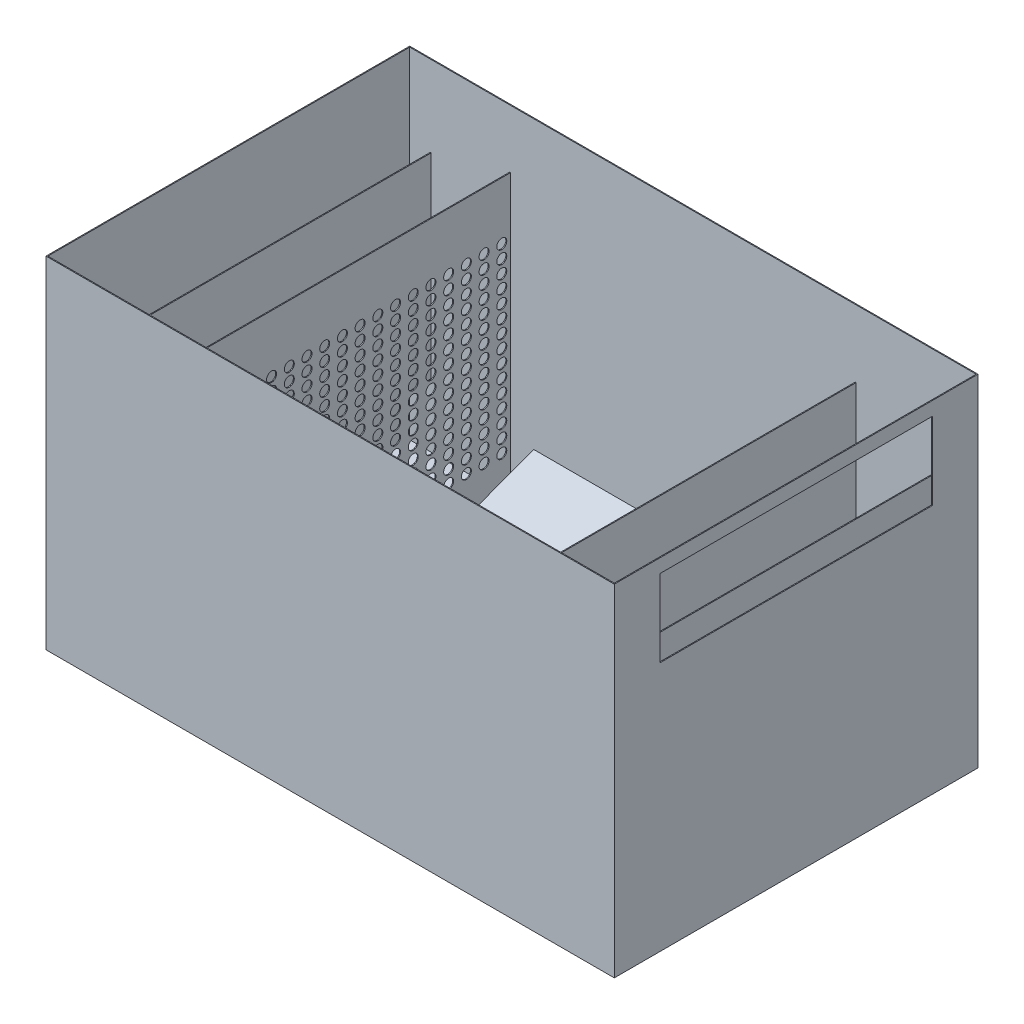
SolidWorks part; units mm, degrees
ref_plane "Спереди" through (0, 0, 0) normal (0, 0, 1) x (1, 0, 0)
ref_plane "Сверху" through (0, 0, 0) normal (0, 1, 0) x (1, 0, 0)
ref_plane "Справа" through (0, 0, 0) normal (1, 0, 0) x (0, 0, -1)
sketch "MASTER_FOOTPRINT" plane through (0, 0, 0) normal (0, 1, 0) x (1, 0, 0)
  line L1 (0, 0) -> (1250, 0)
  line L2 (0, 0) -> (0, 800)
  line L3 (0, 800) -> (1250, 800)
  line L4 (1250, 0) -> (1250, 800)
  dimension "D1" = 1250
  dimension "D2" = 800
extrude "BATH_BASE_PLATE" add sketch "MASTER_FOOTPRINT" along normal blind 750
shell "BATH_SHELL_2MM" thickness 2
sketch "Эскиз1" plane through (0, 0, 0) normal (1, 0, 0) x (0, 0, -1)
  circle A0 centre (400, 420) radius 50
extrude "INLET_D100_OPENING" cut sketch "Эскиз1" along normal blind 10
sketch "Эскиз2" plane through (0, 0, 0) normal (1, 0, 0) x (0, 0, -1)
  line L1 (80, 220) -> (720, 220)
  line L2 (80, 220) -> (80, 650)
  line L3 (80, 650) -> (720, 650)
  line L4 (720, 220) -> (720, 650)
extrude "INLET_IMPACT_BAFFLE" add sketch "Эскиз2" along normal blind 2 from offset 125 separate body
sketch "Эскиз3" plane through (0, 0, 0) normal (1, 0, 0) x (0, 0, -1)
  line L1 (30, 2) -> (770, 2)
  line L2 (30, 2) -> (30, 650)
  line L3 (30, 650) -> (770, 650)
  line L4 (770, 2) -> (770, 650)
  circle A0 centre (49.4737, 125) radius 11
  circle A1 centre (49.4737, 153.5) radius 11
  circle A2 centre (49.4737, 182) radius 11
  circle A3 centre (49.4737, 210.5) radius 11
  circle A4 centre (49.4737, 239) radius 11
  circle A5 centre (49.4737, 267.5) radius 11
  circle A6 centre (49.4737, 296) radius 11
  circle A7 centre (49.4737, 324.5) radius 11
  circle A8 centre (49.4737, 353) radius 11
  circle A9 centre (49.4737, 381.5) radius 11
  circle A10 centre (49.4737, 410) radius 11
  circle A11 centre (49.4737, 438.5) radius 11
  circle A12 centre (49.4737, 467) radius 11
  circle A13 centre (49.4737, 495.5) radius 11
  circle A14 centre (49.4737, 524) radius 11
  circle A15 centre (88.4211, 125) radius 11
  circle A16 centre (88.4211, 153.5) radius 11
  circle A17 centre (88.4211, 182) radius 11
  circle A18 centre (88.4211, 210.5) radius 11
  circle A19 centre (88.4211, 239) radius 11
  circle A20 centre (88.4211, 267.5) radius 11
  circle A21 centre (88.4211, 296) radius 11
  circle A22 centre (88.4211, 324.5) radius 11
  circle A23 centre (88.4211, 353) radius 11
  circle A24 centre (88.4211, 381.5) radius 11
  circle A25 centre (88.4211, 410) radius 11
  circle A26 centre (88.4211, 438.5) radius 11
  circle A27 centre (88.4211, 467) radius 11
  circle A28 centre (88.4211, 495.5) radius 11
  circle A29 centre (88.4211, 524) radius 11
  circle A30 centre (127.3684, 125) radius 11
  circle A31 centre (127.3684, 153.5) radius 11
  circle A32 centre (127.3684, 182) radius 11
  circle A33 centre (127.3684, 210.5) radius 11
  circle A34 centre (127.3684, 239) radius 11
  circle A35 centre (127.3684, 267.5) radius 11
  circle A36 centre (127.3684, 296) radius 11
  circle A37 centre (127.3684, 324.5) radius 11
  circle A38 centre (127.3684, 353) radius 11
  circle A39 centre (127.3684, 381.5) radius 11
  circle A40 centre (127.3684, 410) radius 11
  circle A41 centre (127.3684, 438.5) radius 11
  circle A42 centre (127.3684, 467) radius 11
  circle A43 centre (127.3684, 495.5) radius 11
  circle A44 centre (127.3684, 524) radius 11
  circle A45 centre (166.3158, 125) radius 11
  circle A46 centre (166.3158, 153.5) radius 11
  circle A47 centre (166.3158, 182) radius 11
  circle A48 centre (166.3158, 210.5) radius 11
  circle A49 centre (166.3158, 239) radius 11
  circle A50 centre (166.3158, 267.5) radius 11
  circle A51 centre (166.3158, 296) radius 11
  circle A52 centre (166.3158, 324.5) radius 11
  circle A53 centre (166.3158, 353) radius 11
  circle A54 centre (166.3158, 381.5) radius 11
  circle A55 centre (166.3158, 410) radius 11
  circle A56 centre (166.3158, 438.5) radius 11
  circle A57 centre (166.3158, 467) radius 11
  circle A58 centre (166.3158, 495.5) radius 11
  circle A59 centre (166.3158, 524) radius 11
  circle A60 centre (205.2632, 125) radius 11
  circle A61 centre (205.2632, 153.5) radius 11
  circle A62 centre (205.2632, 182) radius 11
  circle A63 centre (205.2632, 210.5) radius 11
  circle A64 centre (205.2632, 239) radius 11
  circle A65 centre (205.2632, 267.5) radius 11
  circle A66 centre (205.2632, 296) radius 11
  circle A67 centre (205.2632, 324.5) radius 11
  circle A68 centre (205.2632, 353) radius 11
  circle A69 centre (205.2632, 381.5) radius 11
  circle A70 centre (205.2632, 410) radius 11
  circle A71 centre (205.2632, 438.5) radius 11
  circle A72 centre (205.2632, 467) radius 11
  circle A73 centre (205.2632, 495.5) radius 11
  circle A74 centre (205.2632, 524) radius 11
  circle A75 centre (244.2105, 125) radius 11
  circle A76 centre (244.2105, 153.5) radius 11
  circle A77 centre (244.2105, 182) radius 11
  circle A78 centre (244.2105, 210.5) radius 11
  circle A79 centre (244.2105, 239) radius 11
  circle A80 centre (244.2105, 267.5) radius 11
  circle A81 centre (244.2105, 296) radius 11
  circle A82 centre (244.2105, 324.5) radius 11
  circle A83 centre (244.2105, 353) radius 11
  circle A84 centre (244.2105, 381.5) radius 11
  circle A85 centre (244.2105, 410) radius 11
  circle A86 centre (244.2105, 438.5) radius 11
  circle A87 centre (244.2105, 467) radius 11
  circle A88 centre (244.2105, 495.5) radius 11
  circle A89 centre (244.2105, 524) radius 11
  circle A90 centre (283.1579, 125) radius 11
  circle A91 centre (283.1579, 153.5) radius 11
  circle A92 centre (283.1579, 182) radius 11
  circle A93 centre (283.1579, 210.5) radius 11
  circle A94 centre (283.1579, 239) radius 11
  circle A95 centre (283.1579, 267.5) radius 11
  circle A96 centre (283.1579, 296) radius 11
  circle A97 centre (283.1579, 324.5) radius 11
  circle A98 centre (283.1579, 353) radius 11
  circle A99 centre (283.1579, 381.5) radius 11
  circle A100 centre (283.1579, 410) radius 11
  circle A101 centre (283.1579, 438.5) radius 11
  circle A102 centre (283.1579, 467) radius 11
  circle A103 centre (283.1579, 495.5) radius 11
  circle A104 centre (283.1579, 524) radius 11
  circle A105 centre (322.1053, 125) radius 11
  circle A106 centre (322.1053, 153.5) radius 11
  circle A107 centre (322.1053, 182) radius 11
  circle A108 centre (322.1053, 210.5) radius 11
  circle A109 centre (322.1053, 239) radius 11
  circle A110 centre (322.1053, 267.5) radius 11
  circle A111 centre (322.1053, 296) radius 11
  circle A112 centre (322.1053, 324.5) radius 11
  circle A113 centre (322.1053, 353) radius 11
  circle A114 centre (322.1053, 381.5) radius 11
  circle A115 centre (322.1053, 410) radius 11
  circle A116 centre (322.1053, 438.5) radius 11
  circle A117 centre (322.1053, 467) radius 11
  circle A118 centre (322.1053, 495.5) radius 11
  circle A119 centre (322.1053, 524) radius 11
  circle A120 centre (361.0526, 125) radius 11
  circle A121 centre (361.0526, 153.5) radius 11
  circle A122 centre (361.0526, 182) radius 11
  circle A123 centre (361.0526, 210.5) radius 11
  circle A124 centre (361.0526, 239) radius 11
  circle A125 centre (361.0526, 267.5) radius 11
  circle A126 centre (361.0526, 296) radius 11
  circle A127 centre (361.0526, 324.5) radius 11
  circle A128 centre (361.0526, 353) radius 11
  circle A129 centre (361.0526, 381.5) radius 11
  circle A130 centre (361.0526, 410) radius 11
  circle A131 centre (361.0526, 438.5) radius 11
  circle A132 centre (361.0526, 467) radius 11
  circle A133 centre (361.0526, 495.5) radius 11
  circle A134 centre (361.0526, 524) radius 11
  circle A135 centre (400, 125) radius 11
  circle A136 centre (400, 153.5) radius 11
  circle A137 centre (400, 182) radius 11
  circle A138 centre (400, 210.5) radius 11
  circle A139 centre (400, 239) radius 11
  circle A140 centre (400, 267.5) radius 11
  circle A141 centre (400, 296) radius 11
  circle A142 centre (400, 324.5) radius 11
  circle A143 centre (400, 353) radius 11
  circle A144 centre (400, 381.5) radius 11
  circle A145 centre (400, 410) radius 11
  circle A146 centre (400, 438.5) radius 11
  circle A147 centre (400, 467) radius 11
  circle A148 centre (400, 495.5) radius 11
  circle A149 centre (400, 524) radius 11
  circle A150 centre (438.9474, 125) radius 11
  circle A151 centre (438.9474, 153.5) radius 11
  circle A152 centre (438.9474, 182) radius 11
  circle A153 centre (438.9474, 210.5) radius 11
  circle A154 centre (438.9474, 239) radius 11
  circle A155 centre (438.9474, 267.5) radius 11
  circle A156 centre (438.9474, 296) radius 11
  circle A157 centre (438.9474, 324.5) radius 11
  circle A158 centre (438.9474, 353) radius 11
  circle A159 centre (438.9474, 381.5) radius 11
  circle A160 centre (438.9474, 410) radius 11
  circle A161 centre (438.9474, 438.5) radius 11
  circle A162 centre (438.9474, 467) radius 11
  circle A163 centre (438.9474, 495.5) radius 11
  circle A164 centre (438.9474, 524) radius 11
  circle A165 centre (477.8947, 125) radius 11
  circle A166 centre (477.8947, 153.5) radius 11
  circle A167 centre (477.8947, 182) radius 11
  circle A168 centre (477.8947, 210.5) radius 11
  circle A169 centre (477.8947, 239) radius 11
  circle A170 centre (477.8947, 267.5) radius 11
  circle A171 centre (477.8947, 296) radius 11
  circle A172 centre (477.8947, 324.5) radius 11
  circle A173 centre (477.8947, 353) radius 11
  circle A174 centre (477.8947, 381.5) radius 11
  circle A175 centre (477.8947, 410) radius 11
  circle A176 centre (477.8947, 438.5) radius 11
  circle A177 centre (477.8947, 467) radius 11
  circle A178 centre (477.8947, 495.5) radius 11
  circle A179 centre (477.8947, 524) radius 11
  circle A180 centre (516.8421, 125) radius 11
  circle A181 centre (516.8421, 153.5) radius 11
  circle A182 centre (516.8421, 182) radius 11
  circle A183 centre (516.8421, 210.5) radius 11
  circle A184 centre (516.8421, 239) radius 11
  circle A185 centre (516.8421, 267.5) radius 11
  circle A186 centre (516.8421, 296) radius 11
  circle A187 centre (516.8421, 324.5) radius 11
  circle A188 centre (516.8421, 353) radius 11
  circle A189 centre (516.8421, 381.5) radius 11
  circle A190 centre (516.8421, 410) radius 11
  circle A191 centre (516.8421, 438.5) radius 11
  circle A192 centre (516.8421, 467) radius 11
  circle A193 centre (516.8421, 495.5) radius 11
  circle A194 centre (516.8421, 524) radius 11
  circle A195 centre (555.7895, 125) radius 11
  circle A196 centre (555.7895, 153.5) radius 11
  circle A197 centre (555.7895, 182) radius 11
  circle A198 centre (555.7895, 210.5) radius 11
  circle A199 centre (555.7895, 239) radius 11
  circle A200 centre (555.7895, 267.5) radius 11
  circle A201 centre (555.7895, 296) radius 11
  circle A202 centre (555.7895, 324.5) radius 11
  circle A203 centre (555.7895, 353) radius 11
  circle A204 centre (555.7895, 381.5) radius 11
  circle A205 centre (555.7895, 410) radius 11
  circle A206 centre (555.7895, 438.5) radius 11
  circle A207 centre (555.7895, 467) radius 11
  circle A208 centre (555.7895, 495.5) radius 11
  circle A209 centre (555.7895, 524) radius 11
  circle A210 centre (594.7368, 125) radius 11
  circle A211 centre (594.7368, 153.5) radius 11
  circle A212 centre (594.7368, 182) radius 11
  circle A213 centre (594.7368, 210.5) radius 11
  circle A214 centre (594.7368, 239) radius 11
  circle A215 centre (594.7368, 267.5) radius 11
  circle A216 centre (594.7368, 296) radius 11
  circle A217 centre (594.7368, 324.5) radius 11
  circle A218 centre (594.7368, 353) radius 11
  circle A219 centre (594.7368, 381.5) radius 11
  circle A220 centre (594.7368, 410) radius 11
  circle A221 centre (594.7368, 438.5) radius 11
  circle A222 centre (594.7368, 467) radius 11
  circle A223 centre (594.7368, 495.5) radius 11
  circle A224 centre (594.7368, 524) radius 11
  circle A225 centre (633.6842, 125) radius 11
  circle A226 centre (633.6842, 153.5) radius 11
  circle A227 centre (633.6842, 182) radius 11
  circle A228 centre (633.6842, 210.5) radius 11
  circle A229 centre (633.6842, 239) radius 11
  circle A230 centre (633.6842, 267.5) radius 11
  circle A231 centre (633.6842, 296) radius 11
  circle A232 centre (633.6842, 324.5) radius 11
  circle A233 centre (633.6842, 353) radius 11
  circle A234 centre (633.6842, 381.5) radius 11
  circle A235 centre (633.6842, 410) radius 11
  circle A236 centre (633.6842, 438.5) radius 11
  circle A237 centre (633.6842, 467) radius 11
  circle A238 centre (633.6842, 495.5) radius 11
  circle A239 centre (633.6842, 524) radius 11
  circle A240 centre (672.6316, 125) radius 11
  circle A241 centre (672.6316, 153.5) radius 11
  circle A242 centre (672.6316, 182) radius 11
  circle A243 centre (672.6316, 210.5) radius 11
  circle A244 centre (672.6316, 239) radius 11
  circle A245 centre (672.6316, 267.5) radius 11
  circle A246 centre (672.6316, 296) radius 11
  circle A247 centre (672.6316, 324.5) radius 11
  circle A248 centre (672.6316, 353) radius 11
  circle A249 centre (672.6316, 381.5) radius 11
  circle A250 centre (672.6316, 410) radius 11
  circle A251 centre (672.6316, 438.5) radius 11
  circle A252 centre (672.6316, 467) radius 11
  circle A253 centre (672.6316, 495.5) radius 11
  circle A254 centre (672.6316, 524) radius 11
  circle A255 centre (711.5789, 125) radius 11
  circle A256 centre (711.5789, 153.5) radius 11
  circle A257 centre (711.5789, 182) radius 11
  circle A258 centre (711.5789, 210.5) radius 11
  circle A259 centre (711.5789, 239) radius 11
  circle A260 centre (711.5789, 267.5) radius 11
  circle A261 centre (711.5789, 296) radius 11
  circle A262 centre (711.5789, 324.5) radius 11
  circle A263 centre (711.5789, 353) radius 11
  circle A264 centre (711.5789, 381.5) radius 11
  circle A265 centre (711.5789, 410) radius 11
  circle A266 centre (711.5789, 438.5) radius 11
  circle A267 centre (711.5789, 467) radius 11
  circle A268 centre (711.5789, 495.5) radius 11
  circle A269 centre (711.5789, 524) radius 11
  circle A270 centre (750.5263, 125) radius 11
  circle A271 centre (750.5263, 153.5) radius 11
  circle A272 centre (750.5263, 182) radius 11
  circle A273 centre (750.5263, 210.5) radius 11
  circle A274 centre (750.5263, 239) radius 11
  circle A275 centre (750.5263, 267.5) radius 11
  circle A276 centre (750.5263, 296) radius 11
  circle A277 centre (750.5263, 324.5) radius 11
  circle A278 centre (750.5263, 353) radius 11
  circle A279 centre (750.5263, 381.5) radius 11
  circle A280 centre (750.5263, 410) radius 11
  circle A281 centre (750.5263, 438.5) radius 11
  circle A282 centre (750.5263, 467) radius 11
  circle A283 centre (750.5263, 495.5) radius 11
  circle A284 centre (750.5263, 524) radius 11
extrude "DISTRIBUTOR_D22" add sketch "Эскиз3" along normal blind 2 from offset 250 separate body
sketch "Эскиз4" plane through (0, 0, 0) normal (1, 0, 0) x (0, 0, -1)
  line L1 (50, 320) -> (750, 320)
  line L2 (50, 320) -> (50, 650)
  line L3 (50, 650) -> (750, 650)
  line L4 (750, 320) -> (750, 650)
extrude "OUTLET_SUBMERGED_BAFFLE" add sketch "Эскиз4" along normal blind 2 from offset 1030 separate body
sketch "Эскиз5" plane through (0, 0, 0) normal (1, 0, 0) x (0, 0, -1)
  line L1 (5, 2) -> (795, 2)
  line L2 (5, 2) -> (5, 550)
  line L3 (5, 550) -> (795, 550)
  line L4 (795, 2) -> (795, 550)
extrude "OVERFLOW_WEIR_Z550" add sketch "Эскиз5" along normal blind 2 from offset 1190 separate body
sketch "Эскиз6" plane through (0, 0, 0) normal (1, 0, 0) x (0, 0, -1)
  line L1 (100, 550) -> (700, 550)
  line L2 (100, 550) -> (100, 720)
  line L3 (100, 720) -> (700, 720)
  line L4 (700, 550) -> (700, 720)
extrude "OUTLET_WEIR_SLOT_W600" cut sketch "Эскиз6" along normal blind 10 from offset 1245
sketch "Эскиз7" plane through (0, 0, 0) normal (1, 0, 0) x (0, 0, -1)
  line L0 (2, -1) -> (2, 120)
  line L1 (2, 120) -> (330, -1)
  line L2 (330, -1) -> (2, -1)
  line L3 (798, -1) -> (798, 120)
  line L4 (798, 120) -> (470, -1)
  line L5 (470, -1) -> (798, -1)
extrude "SLOPED_SEDIMENT_FLOOR" add sketch "Эскиз7" along normal blind 725 from offset 275
sketch3d "SCREW_AXIS_30DEG_REFERENCE"
  line L0 (400, 70, -400) -> (1350, 618.4828, -400)
equation "\"AI_Q_Peak\"= 0.006"
equation "\"AI_B_Bath\" = 800"
equation "\"AI_L_Settle\" = 800"
equation "\"AI_L_Inlet\"= 250"
equation "\"AI_L_Outlet\"= 200"
equation "\"AI_L_Bath\" = 1250"
equation "\"AI_H_Water\"= 550"
equation "\"AI_H_Freeboard\"= 200"
equation "\"AI_H_Bath\"= 750"
equation "\"AI_Shell_Thickness\"= 2"
equation "\"AI_Inlet_DN\"= 100"
equation "\"AI_Weir_Width\"= 600"
equation "\"AI_Inlet_Baffle_Offset\"= 125"
equation "\"AI_Distributor_Open_Area\"= 0.28"
equation "\"AI_Distributor_Hole_Dia\"= 22"
equation "\"AI_Distributor_Blind_Zone\"= 110"
equation "\"AI_Outlet_Baffle_Depth\"= 250"
equation "\"AI_Screw_Diameter\"= 100"
equation "\"AI_Screw_Pitch\"= 100"
equation "\"AI_Screw_Angle\"= 30"
equation "\"AI_Screw_Rpm\"= 15"
equation "\"AI_Screw_Clearance\"= 5"
equation "\"AI_Liner_Thickness\"= 5"
equation "\"AI_Discharge_Height\"= 650"
equation "\"AI_Frame_Height\"= 500"
equation "\"D1@MASTER_FOOTPRINT\" = \"AI_L_Bath\""
equation "\"D2@MASTER_FOOTPRINT\" = \"AI_B_Bath\""
equation "\"D1@BATH_BASE_PLATE\" = \"AI_H_Bath\""
